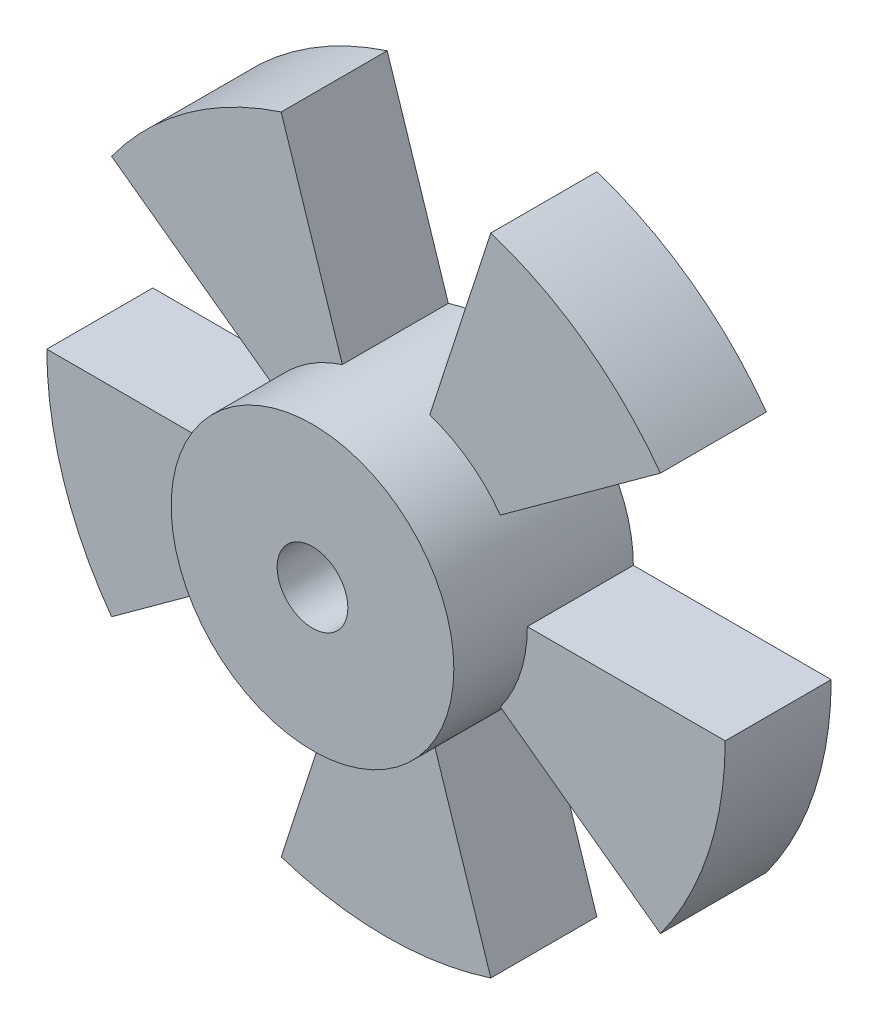
SolidWorks part; units mm, degrees
ref_plane "Płaszczyzna przednia" through (0, 0, 0) normal (0, 0, 1) x (1, 0, 0)
ref_plane "Płaszczyzna górna" through (0, 0, 0) normal (0, 1, 0) x (1, 0, 0)
ref_plane "Płaszczyzna prawa" through (0, 0, 0) normal (1, 0, 0) x (0, 0, -1)
sketch "Szkic1" plane through (0, 0, 0) normal (0, 0, 1) x (1, 0, 0)
  circle A0 centre (0, 0) radius 4.8
  dimension "D1" = 9.6
extrude "Dodanie-wyciągnięcie1" add sketch "Szkic1" along normal blind 1.5
sketch "Szkic2" plane through (0, 0, 1.5) normal (0, 0, 1) x (1, 0, 0)
  circle A0 centre (0, 0) radius 2
extrude "Dodanie-wyciągnięcie2" add sketch "Szkic2" along normal blind 1.5
sketch "Szkic3" plane through (0, 0, 1.5) normal (0, 0, 1) x (1, 0, 0)
  line L0 (0, 0) -> (0, 8.1608) construction
  line L1 (-0.618, 1.9021) -> (-1.4833, 4.5651)
  line L2 (0.618, 1.9021) -> (1.4833, 4.5651)
  circle A0 centre (0, 0) radius 2 construction
  circle A1 centre (0, 0) radius 2
  circle A2 centre (0, 0) radius 4.8 construction
  circle A3 centre (0, 0) radius 4.8
  circle M4 centre (0, 0) radius 2
  circle M5 centre (0, 0) radius 4.8
  dimension "D1" = 36
extrude "Wytnij-wyciągnięcie1" cut sketch "Szkic3" against normal up to next contours L0 A3 L1 M4 | L0 A1 L2 M5
pattern_circular "Szyk kołowy2" count 5 over 360 about axis through (0, 0, 0) along (0, 0, 1) of "Wytnij-wyciągnięcie1"
hole_wizard "Otwór1" positions "Szkic5" profile "Szkic6" legacy end condition through all
sketch "Szkic5" plane through (0, 0, 3) normal (0, 0, 1) x (1, 0, 0)
  point P0 (0, 0)
sketch "Szkic6" plane through (0, 0, 3) normal (1, 0, 0) x (0, -1, 0)
  line L0 (0, 0) -> (0, 3)
  line L1 (0, 3) -> (0.5, 3)
  line L2 (0.5, 3) -> (0.5, 0)
  line L3 (0.5, 0) -> (0, 0)
  line L4 (0, 110) -> (0, -10) construction
  dimension "Średnica" = 1
  dimension "Głębokość" = 3
ref_plane "Plano2" through (0, 0, 3) normal (0, 0, 1) x (1, 0, 0)
sketch "Esboço1" plane through (0, 0, 3) normal (0, 0, 1) x (1, 0, 0)
  circle A0 centre (0, 0) radius 2
  dimension "D1" = 4
extrude "Corte-extrusão1" cut sketch "Esboço1" against normal blind 0.46
